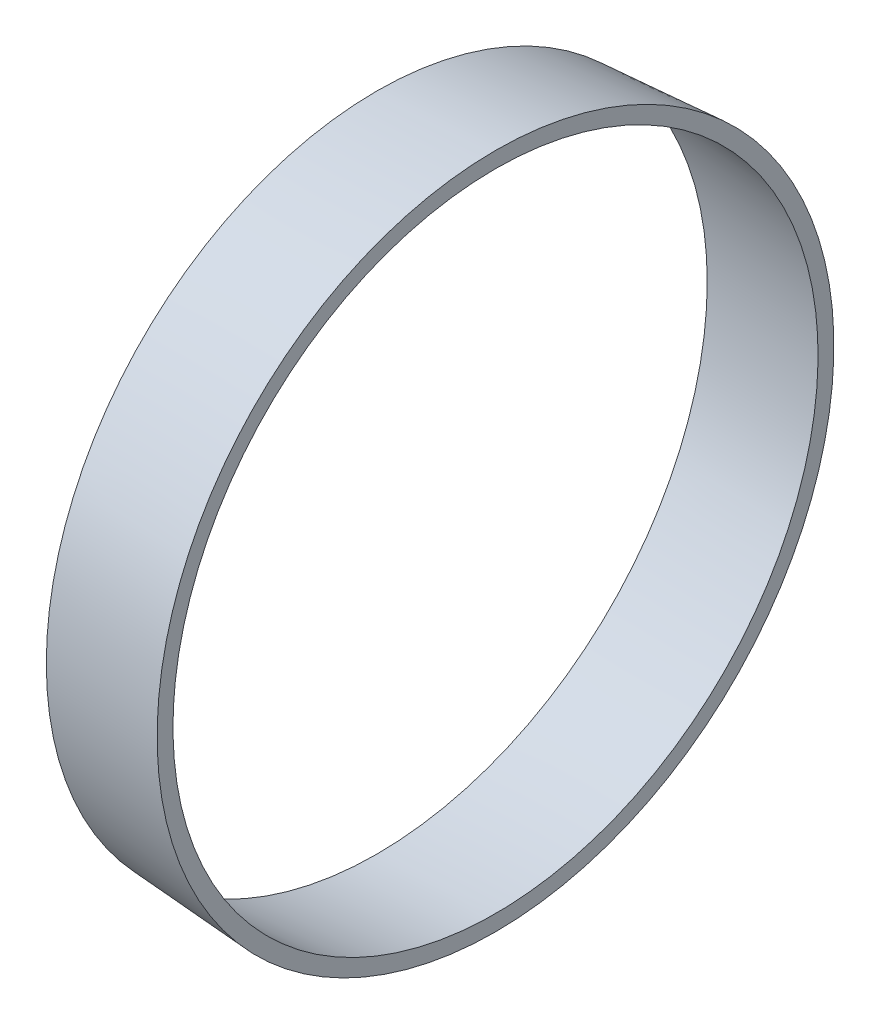
SolidWorks part; units mm, degrees
ref_plane "Front Plane" through (0, 0, 0) normal (0, 0, 1) x (1, 0, 0)
ref_plane "Top Plane" through (0, 0, 0) normal (0, 1, 0) x (1, 0, 0)
ref_plane "Right Plane" through (0, 0, 0) normal (1, 0, 0) x (0, 0, -1)
sketch "Sketch1" plane through (0, 0, 0) normal (0, 0, 1) x (1, 0, 0)
  line L0 (0, 0) -> (2000, 0) construction
  line L1 (100, 1670) -> (700, 1710)
  line L2 (700, 1710) -> (700, 1630)
  line L3 (700, 1630) -> (100, 1670)
revolve "Revolve1" add sketch "Sketch1" angle 360 about L0
